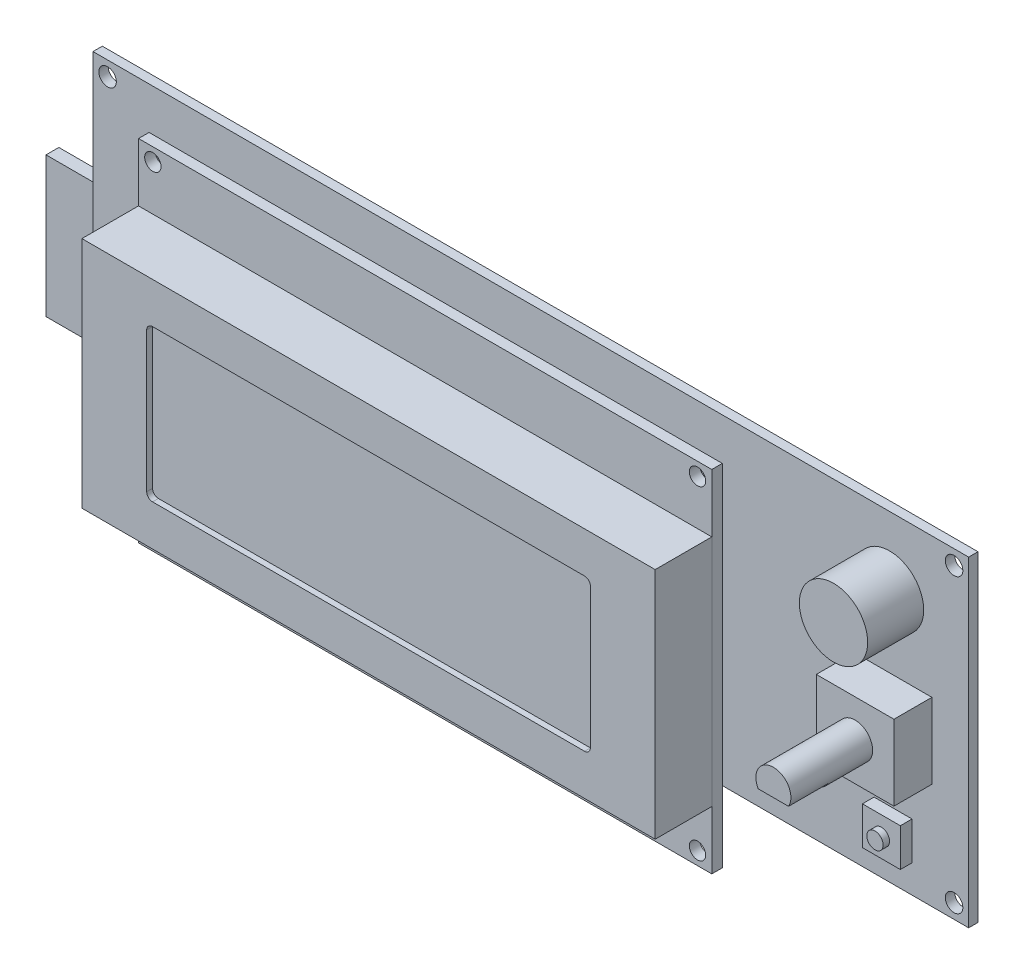
SolidWorks part; units mm, degrees
ref_plane "Front Plane" through (0, 0, 0) normal (0, 0, 1) x (1, 0, 0)
ref_plane "Top Plane" through (0, 0, 0) normal (0, 1, 0) x (1, 0, 0)
ref_plane "Right Plane" through (0, 0, 0) normal (1, 0, 0) x (0, 0, -1)
sketch "Sketch1" plane through (0, 0, 0) normal (0, 0, 1) x (1, 0, 0)
  line L1 (-75, -27.5) -> (75, -27.5)
  line L2 (-75, -27.5) -> (-75, 27.5)
  line L3 (-75, 27.5) -> (75, 27.5)
  line L4 (75, -27.5) -> (75, 27.5)
  line L5 (-75, -27.5) -> (75, 27.5) construction
  line L6 (-75, 27.5) -> (75, -27.5) construction
  point P0 (0, 0)
  dimension "D1" = 150
  dimension "D2" = 55
extrude "PCB" add sketch "Sketch1" against normal blind 1.6
hole_wizard "Ø3.0 (3) Diameter Hole1" positions "Sketch3" profile "Sketch2" hole size "Ø3.0" standard "ANSI Metric"
sketch "Sketch3" plane through (0, 0, 0) normal (0, 0, 1) x (1, 0, 0)
  line L1 (72.5, -25) -> (-72.5, -25)
  line L2 (72.5, -25) -> (72.5, 25)
  line L3 (72.5, 25) -> (-72.5, 25)
  line L4 (-72.5, -25) -> (-72.5, 25)
  line L5 (72.5, -25) -> (-72.5, 25) construction
  line L6 (72.5, 25) -> (-72.5, -25) construction
  line L7 (75, 27.5) -> (-75, 27.5) construction
  line L8 (-75, 27.5) -> (-75, -27.5) construction
  point P0 (-72.5, 25)
  point P2 (72.5, 25)
  point P4 (72.5, -25)
  point P6 (-72.5, -25)
  dimension "D1" = 2.5
  dimension "D2" = 2.5
sketch "Sketch2" plane through (-72.5, 25, 0) normal (1, 0, 0) x (0, -1, 0)
  line L0 (0, 0) -> (0, 4.9013)
  line L1 (0, 4.9013) -> (1.5, 4)
  line L2 (1.5, 4) -> (1.5, 0)
  line L5 (1.5, 0) -> (0, 0)
  line L10 (0, 4.9013) -> (-1.5, 4) construction
  line L11 (0, -6.35) -> (0, 107.95) construction
  dimension "Hole Dia." = 3
  dimension "Hole Depth" = 4
  dimension "Drill Angle" = 118
sketch "Sketch4" plane through (0, 0, -1.6) normal (0, 0, -1) x (-1, 0, 0)
  line L0 (75, -27.5) -> (-75, -27.5) construction
  line L1 (-14.2, 5) -> (6.1, 5)
  line L2 (-14.2, 5) -> (-14.2, -3.8)
  line L3 (-14.2, -3.8) -> (6.1, -3.8)
  line L4 (6.1, 5) -> (6.1, -3.8)
  line L5 (-75, -27.5) -> (-75, 27.5) construction
  dimension "D1" = 20.3
  dimension "D2" = 8.8
  dimension "D3" = 32.5
  dimension "D4" = 60.8
extrude "IDC conn" add sketch "Sketch4" along normal blind 17.5
pattern_linear "LPattern1" count 2 spacing 22.86 along (-1, 0, 0) of "IDC conn"
sketch "Sketch5" plane through (0, 0, -1.6) normal (0, 0, -1) x (-1, 0, 0)
  line L0 (75, 27.5) -> (75, -27.5) construction
  line L1 (75, -19.3) -> (49.3, -19.3)
  line L2 (75, -19.3) -> (75, 7.3)
  line L3 (75, 7.3) -> (49.3, 7.3)
  line L4 (49.3, -19.3) -> (49.3, 7.3)
  line L5 (75, -27.5) -> (-75, -27.5) construction
  dimension "D1" = 26.6
  dimension "D2" = 25.7
  dimension "D3" = 8.2
extrude "SD socket" add sketch "Sketch5" along normal blind 3.3 separate body
sketch "Sketch6" plane through (-75, 0, 0) normal (-1, 0, 0) x (0, 0, 1)
  line L0 (-4.35, 6) -> (-2.15, -18) construction
  line L1 (-4.35, 6) -> (-2.15, 6)
  line L2 (-4.35, 6) -> (-4.35, -18)
  line L3 (-4.35, -18) -> (-2.15, -18)
  line L4 (-2.15, 6) -> (-2.15, -18)
  line L5 (-1.6, 7.3) -> (-4.9, -19.3) construction
  point P9 (-3.25, -6)
  dimension "D1" = 24
  dimension "D2" = 2.2
extrude "SD card" add sketch "Sketch6" along normal blind 10.2
sketch "Sketch7" plane through (0, 0, -1.6) normal (0, 0, -1) x (-1, 0, 0)
  line L0 (-75, 27.5) -> (75, 27.5) construction
  line L1 (75, 27.5) -> (75, 7.3) construction
  line L2 (50.95, 12.85) -> (51.7, 12.85)
  line L3 (50.45, 12.1) -> (50.95, 12.1)
  line L4 (50.45, 12.1) -> (50.45, 12.85)
  line L5 (50.45, 14.1) -> (50.95, 14.1)
  line L6 (50.95, 12.1) -> (50.95, 12.85)
  line L7 (50.45, 12.1) -> (50.95, 14.1) construction
  line L8 (50.45, 14.1) -> (50.95, 12.1) construction
  line L9 (49.7, 12.85) -> (50.45, 12.85)
  line L10 (49.7, 12.85) -> (49.7, 13.35)
  line L11 (49.7, 13.35) -> (50.45, 13.35)
  line L12 (51.7, 12.85) -> (51.7, 13.35)
  line L13 (49.7, 12.85) -> (51.7, 13.35) construction
  line L14 (49.7, 13.35) -> (51.7, 12.85) construction
  line L15 (50.95, 13.35) -> (50.95, 14.1)
  line L16 (50.95, 13.35) -> (51.7, 13.35)
  line L17 (50.45, 13.35) -> (50.45, 14.1)
  circle A0 centre (50.7, 13.1) radius 1.75
  point P10 (50.7, 13.1)
  dimension "D1" = 3.5
  dimension "D2" = 14.4
  dimension "D3" = 24.3
  dimension "D4" = 0.5
  dimension "D5" = 2
extrude "Contrast pot" add sketch "Sketch7" along normal blind 2.5
sketch "Sketch8" plane through (0, 0, -1.6) normal (0, 0, -1) x (-1, 0, 0)
  line L0 (-3.8, 11.0707) -> (-3.8, 14.7293)
  line L1 (-75, 27.5) -> (75, 27.5) construction
  line L2 (-75, -27.5) -> (-75, 27.5) construction
  arc A0 (-3.8, 14.7293) -> (-3.8, 11.0707) centre (-5.235, 12.9) ccw
  dimension "D1" = 2.325
  dimension "D2" = 3.76
  dimension "D3" = 14.6
  dimension "D4" = 71.2
extrude "2N3901" add sketch "Sketch8" along normal blind 7
ref_plane "Plane1" through (0, 0, 4) normal (0, 0, 1) x (1, 0, 0)
sketch "Sketch9" plane through (0, 0, 4) normal (0, 0, 1) x (1, 0, 0)
  line L0 (-75, 27.5) -> (-75, -27.5) construction
  line L1 (-61.4, 24.3) -> (36.8, 24.3)
  line L2 (-61.4, 24.3) -> (-61.4, -35.7)
  line L3 (-61.4, -35.7) -> (36.8, -35.7)
  line L4 (36.8, 24.3) -> (36.8, -35.7)
  line L5 (75, 27.5) -> (-75, 27.5) construction
  dimension "D1" = 60
  dimension "D2" = 98.2
  dimension "D3" = 13.6
  dimension "D4" = 3.2
extrude "LCD PCB" add sketch "Sketch9" along normal blind 1.8 separate body
sketch "Sketch10" plane through (0, 0, 5.8) normal (0, 0, 1) x (1, 0, 0)
  line L0 (-61.4, 24.3) -> (-61.4, -35.7) construction
  line L1 (-61.4, 14.3) -> (36.8, 14.3)
  line L2 (-61.4, 14.3) -> (-61.4, -25.7)
  line L3 (-61.4, -25.7) -> (36.8, -25.7)
  line L4 (36.8, 14.3) -> (36.8, -25.7)
  line L5 (36.8, -35.7) -> (36.8, 24.3) construction
  point P8 (-61.4, -5.7)
  dimension "D1" = 40
extrude "LCD housing" add sketch "Sketch10" along normal blind 9.7 separate body
sketch "Sketch11" plane through (0, 0, 15.5) normal (0, 0, 1) x (1, 0, 0)
  line L0 (-61.4, -25.7) -> (36.8, 14.3) construction
  line L2 (25.7, -18.7) -> (-50.3, -18.7)
  line L3 (25.7, -18.7) -> (25.7, 7.3)
  line L4 (25.7, 7.3) -> (-50.3, 7.3)
  line L5 (-50.3, -18.7) -> (-50.3, 7.3)
  line L6 (25.7, -18.7) -> (-50.3, 7.3) construction
  line L7 (25.7, 7.3) -> (-50.3, -18.7) construction
  point P2 (-12.3, -5.7)
  dimension "D1" = 76
  dimension "D2" = 26
extrude "Cut-Extrude1" cut sketch "Sketch11" against normal blind 1
fillet "Fillet1" radius 1 4 edges at (-50.3, -18.7, 15) (-50.3, 7.3, 15) (25.7, -18.7, 15) (25.7, 7.3, 15)
hole_wizard "Ø2.8 (2.8) Diameter Hole1" positions "Sketch13" profile "Sketch12" hole size "Ø2.8" standard "ANSI Metric"
sketch "Sketch13" plane through (0, 0, 5.8) normal (0, 0, 1) x (1, 0, 0)
  line L1 (34.35, -33.45) -> (-58.95, -33.45)
  line L2 (34.35, -33.45) -> (34.35, 22.05)
  line L3 (34.35, 22.05) -> (-58.95, 22.05)
  line L4 (-58.95, -33.45) -> (-58.95, 22.05)
  line L5 (34.35, -33.45) -> (-58.95, 22.05) construction
  line L6 (34.35, 22.05) -> (-58.95, -33.45) construction
  line L7 (-12.3, -35.7) -> (-12.3, 24.3) construction
  line L8 (-61.4, -35.7) -> (36.8, -35.7) construction
  line L9 (36.8, 24.3) -> (-61.4, 24.3) construction
  point P0 (-58.95, 22.05)
  point P2 (34.35, 22.05)
  point P4 (34.35, -33.45)
  point P6 (-58.95, -33.45)
  point P190 (-12.3, -5.7)
  dimension "D1" = 55.5
  dimension "D2" = 93.3
sketch "Sketch12" plane through (-58.95, 22.05, 5.8) normal (1, 0, 0) x (0, -1, 0)
  line L0 (0, 0) -> (0, 4.8412)
  line L1 (0, 4.8412) -> (1.4, 4)
  line L2 (1.4, 4) -> (1.4, 0)
  line L5 (1.4, 0) -> (0, 0)
  line L10 (0, 4.8412) -> (-1.4, 4) construction
  line L11 (0, -6.35) -> (0, 107.95) construction
  dimension "Hole Dia." = 2.8
  dimension "Hole Depth" = 4
  dimension "Drill Angle" = 118
sketch "Sketch14" plane through (0, 0, 0) normal (0, 0, 1) x (1, 0, 0)
  line L0 (75, 27.5) -> (-75, 27.5) construction
  line L2 (75, -27.5) -> (75, 27.5) construction
  circle A0 centre (61.45, 15.8) radius 5.85
  dimension "D1" = 11.7
  dimension "D2" = 11.7
  dimension "D3" = 7.7
extrude "buzzer" add sketch "Sketch14" along normal blind 9.6
sketch "Sketch15" plane through (0, 0, 0) normal (0, 0, 1) x (1, 0, 0)
  line L0 (75, -27.5) -> (75, 27.5) construction
  line L1 (55.4, -9.35) -> (68.7, -9.35)
  line L2 (55.4, -9.35) -> (55.4, 3.55)
  line L3 (55.4, 3.55) -> (68.7, 3.55)
  line L4 (68.7, -9.35) -> (68.7, 3.55)
  line L5 (55.4, -9.35) -> (68.7, 3.55) construction
  line L6 (55.4, 3.55) -> (68.7, -9.35) construction
  line L7 (75, 27.5) -> (-75, 27.5) construction
  point P0 (62.05, -2.9)
  dimension "D1" = 13.3
  dimension "D2" = 12.9
  dimension "D3" = 30.4
  dimension "D4" = 6.3
extrude "enc body" add sketch "Sketch15" along normal blind 6.5
sketch "Sketch16" plane through (0, 0, 6.5) normal (0, 0, 1) x (1, 0, 0)
  line L0 (55.4, -9.35) -> (68.7, 3.55) construction
  circle A0 centre (62.05, -2.9) radius 3
  dimension "D1" = 3
extrude "enc shaft" add sketch "Sketch16" along normal blind 14
sketch "Sketch17" plane through (0, 0, 20.5) normal (0, 0, 1) x (1, 0, 0)
  line L1 (59.4519, -4.4) -> (64.6481, -4.4)
  line L2 (59.4519, -4.4) -> (59.4519, -5.9)
  line L3 (59.4519, -5.9) -> (64.6481, -5.9)
  line L4 (64.6481, -4.4) -> (64.6481, -5.9)
  circle A0 centre (62.05, -2.9) radius 3 construction
  dimension "D1" = 4.5
extrude "enc shaft flat" cut sketch "Sketch17" against normal blind 6.8
sketch "Sketch18" plane through (0, 0, 0) normal (0, 0, 1) x (1, 0, 0)
  line L0 (62.05, -19.45) -> (62.05, -2.9) construction
  line L1 (58.8, -22.7) -> (65.3, -22.7)
  line L2 (58.8, -22.7) -> (58.8, -16.2)
  line L3 (58.8, -16.2) -> (65.3, -16.2)
  line L4 (65.3, -22.7) -> (65.3, -16.2)
  line L5 (58.8, -22.7) -> (65.3, -16.2) construction
  line L6 (58.8, -16.2) -> (65.3, -22.7) construction
  line L7 (-75, -27.5) -> (75, -27.5) construction
  point P0 (62.05, -19.45)
  dimension "D1" = 6.5
  dimension "D2" = 4.8
extrude "e-stop sw body" add sketch "Sketch18" along normal blind 2
sketch "Sketch19" plane through (0, 0, 2) normal (0, 0, 1) x (1, 0, 0)
  line L0 (58.8, -22.7) -> (65.3, -16.2) construction
  circle A0 centre (62.05, -19.45) radius 1.4
  dimension "D1" = 2.8
extrude "e-stop sw button" add sketch "Sketch19" along normal blind 1.1
